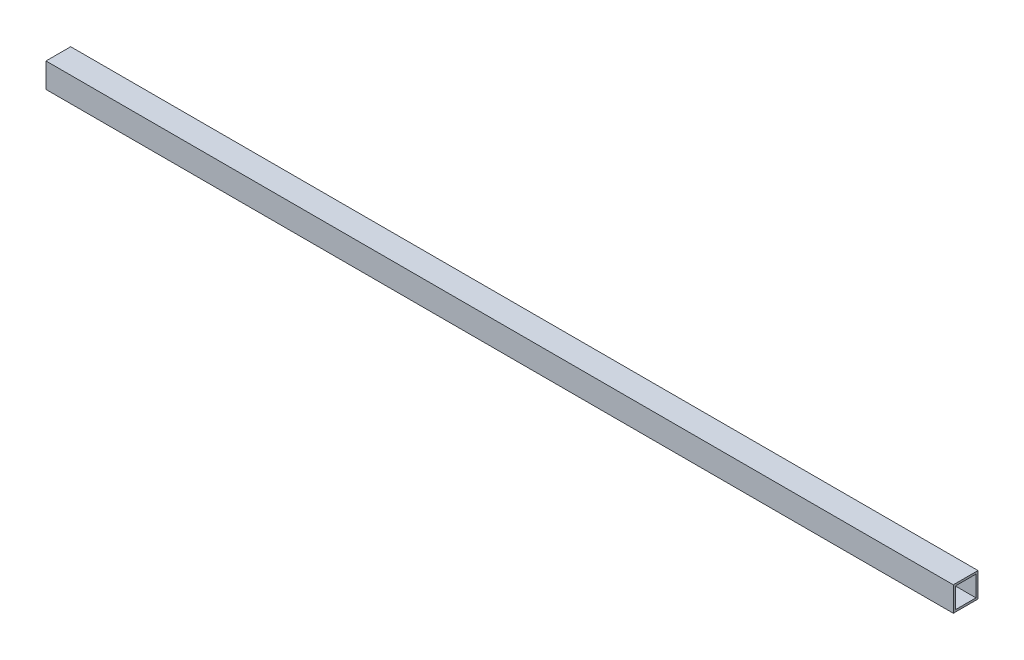
SolidWorks part; units mm, degrees
ref_plane "Front Plane" through (0, 0, 0) normal (0, 0, 1) x (1, 0, 0)
ref_plane "Top Plane" through (0, 0, 0) normal (0, 1, 0) x (1, 0, 0)
ref_plane "Right Plane" through (0, 0, 0) normal (1, 0, 0) x (0, 0, -1)
sketch "Sketch1" plane through (-263.3804, 0, 0) normal (1, 0, 0) x (0, 0, -1)
  line L0 (-848.1605, 3.9434) -> (-832.2855, 3.9434)
  line L1 (-849.748, 5.5309) -> (-830.698, 5.5309)
  line L2 (-849.748, 5.5309) -> (-849.748, -13.5191)
  line L3 (-849.748, -13.5191) -> (-830.698, -13.5191)
  line L4 (-830.698, 5.5309) -> (-830.698, -13.5191)
  line L5 (-832.2855, 3.9434) -> (-832.2855, -11.9316)
  line L6 (-848.1605, -11.9316) -> (-832.2855, -11.9316)
  line L7 (-848.1605, 3.9434) -> (-848.1605, -11.9316)
  dimension "D1" = 19.05
  dimension "D2" = 1.5875
extrude "Boss-Extrude1" add sketch "Sketch1" against normal up to surface (700 mm away)
ref_plane "Plane1" through (0, 0, 840.223) normal (0, 0, 1) x (1, 0, 0)
ref_plane "Plane2" through (0, -3.9941, 0) normal (0, 1, 0) x (1, 0, 0)
